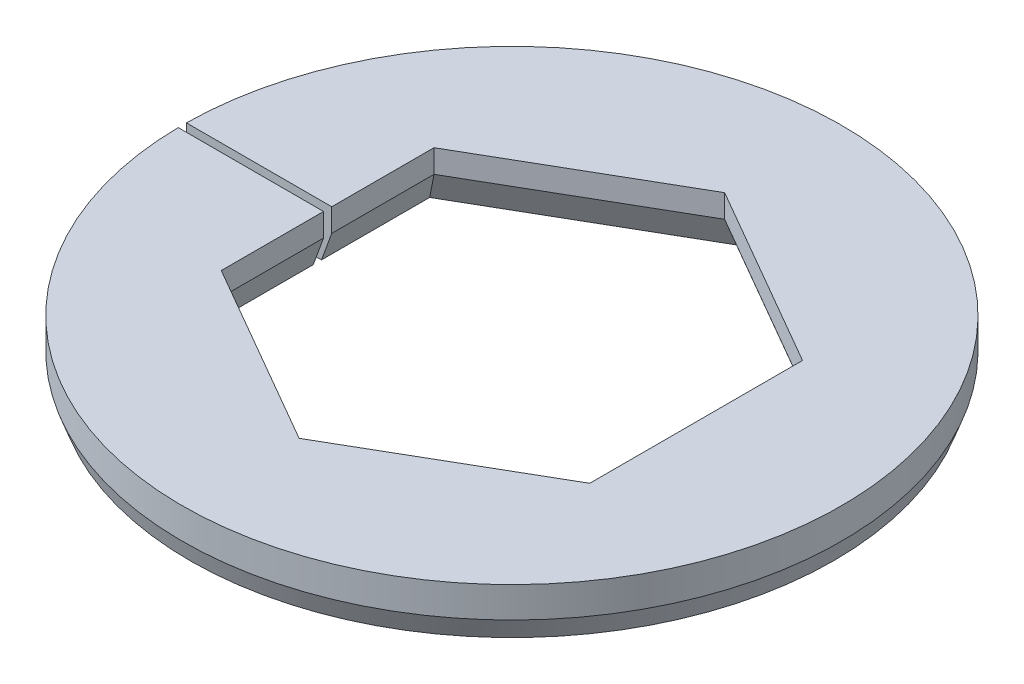
SolidWorks part; units mm, degrees
ref_plane "Спереди" through (0, 0, 0) normal (0, 0, 1) x (1, 0, 0)
ref_plane "Сверху" through (0, 0, 0) normal (0, 1, 0) x (1, 0, 0)
ref_plane "Справа" through (0, 0, 0) normal (1, 0, 0) x (0, 0, -1)
sketch "Эскиз1" plane through (0, 0, 0) normal (0, 1, 0) x (1, 0, 0)
  circle A0 centre (0, 0) radius 16.1
  dimension "D1" = 32.2
extrude "Бобышка-Вытянуть1" add sketch "Эскиз1" along normal blind 2.5
sketch "Эскиз2" plane through (0, 2.5, 0) normal (0, 1, 0) x (1, 0, 0)
  line L1 (0, 10.3923) -> (-9, 5.1962)
  line L2 (-9, 5.1962) -> (-9, -5.1962)
  line L3 (-9, -5.1962) -> (0, -10.3923)
  line L4 (0, -10.3923) -> (9, -5.1962)
  line L5 (9, -5.1962) -> (9, 5.1962)
  line L6 (9, 5.1962) -> (0, 10.3923)
  circle A0 centre (0, 0) radius 9 construction
  dimension "D1" = 18
extrude "Вырез-Вытянуть1" cut sketch "Эскиз2" against normal through all
sketch "Эскиз3" plane through (0, 2.5, 0) normal (0, 1, 0) x (1, 0, 0)
  line L0 (-9, 5.1962) -> (-9, -5.1962) construction
  line L1 (-9, -0.2) -> (-16.1, -0.2)
  line L2 (-9, -0.2) -> (-9, 0.2)
  line L3 (-9, 0.2) -> (-16.1, 0.2)
  line L4 (-16.1, -0.2) -> (-16.1, 0.2)
  circle A0 centre (0, 0) radius 16.1 construction
  point P4 (-9, 0)
  dimension "D1" = 0.4
extrude "Вырез-Вытянуть2" cut sketch "Эскиз3" against normal through all
chamfer "Фаска1" distance 1 angle 20 1 edges at (16.1, 0, 0)
chamfer "Фаска2" distance 0.5 angle 70 7 edges at (-9, 0, 2.6981) (-9, 0, -2.6981) (-4.5, 0, -7.7942) (4.5, 0, -7.7942) (9, 0, 0) (4.5, 0, 7.7942) (-4.5, 0, 7.7942)
